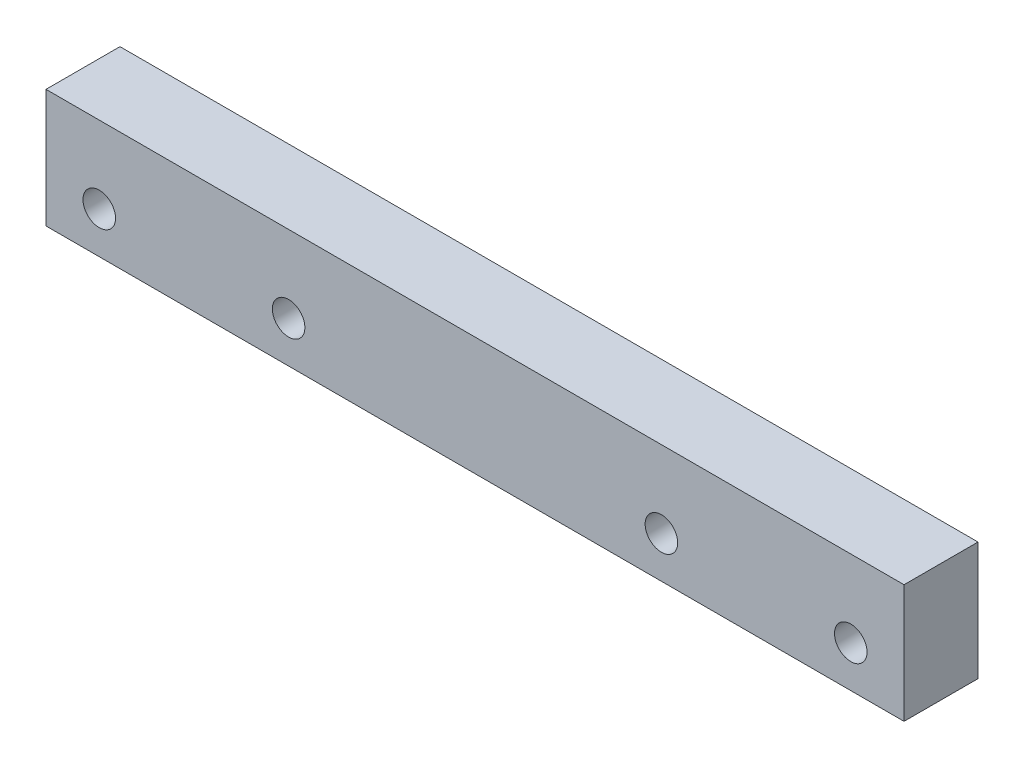
SolidWorks part; units mm, degrees
ref_plane "前视基准面" through (0, 0, 0) normal (0, 0, 1) x (1, 0, 0)
ref_plane "上视基准面" through (0, 0, 0) normal (0, 1, 0) x (1, 0, 0)
ref_plane "右视基准面" through (0, 0, 0) normal (1, 0, 0) x (0, 0, -1)
other "Configuration Table"
sketch "草图1" plane through (0, 0, 0) normal (0, 0, 1) x (1, 0, 0)
  line L1 (-72.5, -10) -> (72.5, -10)
  line L2 (-72.5, -10) -> (-72.5, 10)
  line L3 (-72.5, 10) -> (72.5, 10)
  line L4 (72.5, -10) -> (72.5, 10)
  line L5 (-72.5, -10) -> (72.5, 10) construction
  line L6 (-72.5, 10) -> (72.5, -10) construction
  point P0 (0, 0)
  dimension "D1" = 20
  dimension "D2" = 145
extrude "凸台-拉伸1" add sketch "草图1" along normal blind 12.5
sketch "草图2" plane through (0, 0, 0) normal (0, 0, -1) x (-1, 0, 0)
  line L0 (-72.5, -10) -> (-72.5, 10) construction
  line L1 (-72.5, 10) -> (72.5, 10) construction
  line L2 (0, 0) -> (0, -10) construction
  line L3 (72.5, -10) -> (-72.5, -10) construction
  circle A0 centre (-63.5, -3) radius 2.75
  circle A1 centre (-31.5, -3) radius 2.75
  circle A2 centre (31.5, -3) radius 2.75
  circle A3 centre (63.5, -3) radius 2.75
  dimension "D3" = 5.5
  dimension "D4" = 32
  dimension "D1" = 9
  dimension "D2" = 13
extrude "切除-拉伸1" cut sketch "草图2" against normal up to surface (12.5 mm away) up to face at (0, 0, 12.5)
